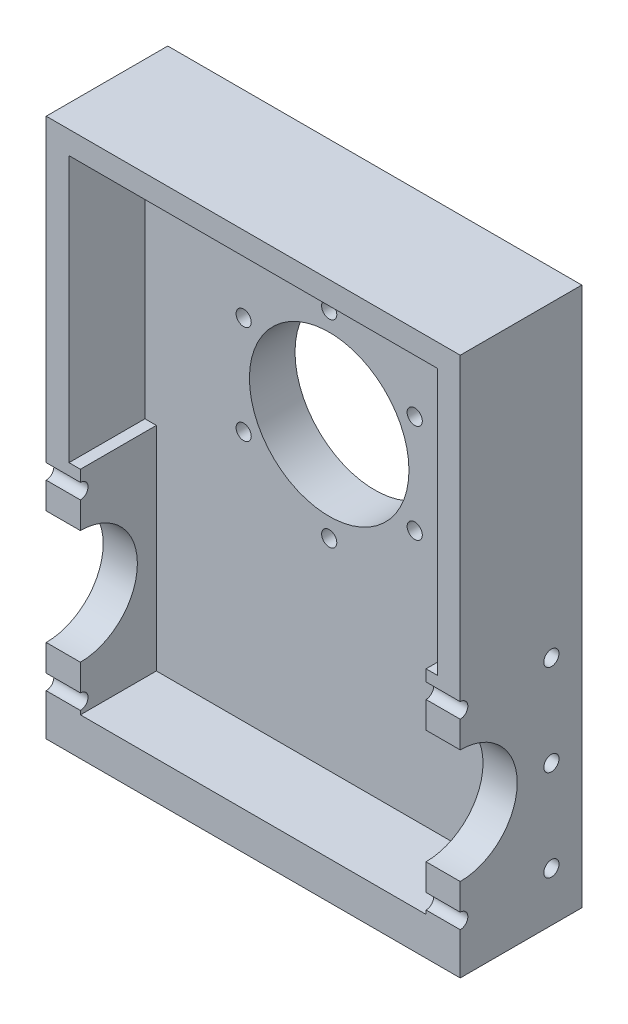
SolidWorks part; units mm, degrees
ref_plane "Front Plane" through (0, 0, 0) normal (0, 0, 1) x (1, 0, 0)
ref_plane "Top Plane" through (0, 0, 0) normal (0, 1, 0) x (1, 0, 0)
ref_plane "Right Plane" through (0, 0, 0) normal (1, 0, 0) x (0, 0, -1)
sketch "Sketch1" plane through (0, 0, 0) normal (0, 0, 1) x (1, 0, 0)
  line L0 (0, 0) -> (0, -52) construction
  line L2 (-48.5, -65) -> (48.5, -65)
  line L3 (-48.5, -65) -> (-48.5, 65)
  line L4 (-48.5, 65) -> (48.5, 65)
  line L5 (48.5, -65) -> (48.5, 65)
  line L6 (-48.5, -65) -> (48.5, 65) construction
  line L7 (-48.5, 65) -> (48.5, -65) construction
  dimension "D1" = 52
  dimension "D2" = 130
  dimension "D3" = 97
extrude "Boss-Extrude1" add sketch "Sketch1" along normal blind 12
sketch "Sketch8" plane through (0, 0, 12) normal (0, 0, 1) x (1, 0, 0)
  line L0 (0, 65) -> (0, 18) construction
  line L1 (48.5, 65) -> (-48.5, 65) construction
  circle A0 centre (0, 18) radius 43.5
  dimension "D2" = 87
  dimension "D1" = 47
sketch "Sketch9" plane through (0, 0, 12) normal (0, 0, 1) x (1, 0, 0)
  line L0 (0, 65) -> (0, 18) construction
  circle A0 centre (0, 18) radius 21
  circle A1 centre (0, 44) radius 2
  circle A7 centre (22.5167, 31) radius 2
  circle A8 centre (22.5167, 5) radius 2
  circle A9 centre (0, -8) radius 2
  circle A10 centre (-22.5167, 5) radius 2
  circle A11 centre (-22.5167, 31) radius 2
  point P19 (8.6603, 13)
  point P21 (0, 18)
  dimension "D1" = 42
  dimension "D2" = 4
  dimension "D3" = 26
  dimension "D4" = 6
extrude "Cut-Extrude2" cut sketch "Sketch9" against normal blind 12
sketch "Sketch11" plane through (0, 0, 0) normal (0, 0, 1) x (1, 0, 0)
  line L0 (-54.5, 71) -> (54.5, 71)
  line L1 (-48.5, -65) -> (48.5, -65)
  line L2 (-48.5, -65) -> (-48.5, 65)
  line L3 (-48.5, 65) -> (48.5, 65)
  line L4 (48.5, -65) -> (48.5, 65)
  line L5 (-48.5, -65) -> (48.5, 65) construction
  line L6 (-48.5, 65) -> (48.5, -65) construction
  line L7 (54.5, -71) -> (54.5, 71)
  line L8 (-54.5, -71) -> (54.5, -71)
  line L9 (-54.5, -71) -> (-54.5, 71)
  point P0 (0, 0)
  dimension "D1" = 6
extrude "Boss-Extrude4" add sketch "Sketch11" along normal blind 32
sketch "Sketch14" plane through (-54.5, 0, 0) normal (-1, 0, 0) x (0, 0, 1)
  line L0 (32, 71) -> (32, -71) construction
  line L1 (32, -71) -> (0, -71) construction
  circle A0 centre (32, -34) radius 15
  point P20 (32, -34)
  point P21 (34.6699, -46.5)
  point P22 (35.5, -27.9378)
  dimension "D1" = 30
  dimension "D2" = 37
sketch "Sketch18" plane through (-48.5, 0, 0) normal (1, 0, 0) x (0, 0, -1)
  line L0 (-12, 65) -> (-12, -65) construction
  line L1 (-32, -65) -> (-12, -65)
  line L2 (-32, -65) -> (-32, -5)
  line L3 (-32, -5) -> (-12, -5)
  line L4 (-12, -65) -> (-12, -5)
  dimension "D1" = 60
extrude "Boss-Extrude5" add sketch "Sketch18" along normal blind 3
mirror "Mirror1" about plane through (0, 0, 0) normal (1, 0, 0) of "Boss-Extrude5"
extrude "Cut-Extrude5" cut sketch "Sketch14" against normal through all
sketch "Sketch20" plane through (0, -65, 0) normal (0, 1, 0) x (1, 0, 0)
  line L1 (-45.5, -12) -> (45.5, -12)
  line L2 (-45.5, -12) -> (-45.5, -32)
  line L3 (-45.5, -32) -> (45.5, -32)
  line L4 (45.5, -12) -> (45.5, -32)
extrude "Boss-Extrude6" add sketch "Sketch20" along normal blind 4
sketch "Sketch21" plane through (-54.5, 0, 0) normal (-1, 0, 0) x (0, 0, 1)
  line L0 (32, -34) -> (32, -10) construction
  line L1 (32, 71) -> (32, -19) construction
  line L2 (0, -34) -> (64.9981, -34) construction
  line L3 (0, 71) -> (0, -71) construction
  circle A0 centre (32, -10) radius 2
  circle A1 centre (8, -10) radius 2
  circle A2 centre (56, -10) radius 2
  circle A3 centre (56, -58) radius 2
  circle A4 centre (32, -58) radius 2
  circle A5 centre (8, -58) radius 2
  circle A6 centre (8, -34) radius 2
  dimension "D2" = 4
  dimension "D3" = 4
  dimension "D4" = 24
  dimension "D5" = 4
  dimension "D6" = 24
  dimension "D7" = 4
  dimension "D1" = 24
extrude "Cut-Extrude6" cut sketch "Sketch21" against normal blind 9
mirror "Mirror2" about plane through (0, 0, 0) normal (1, 0, 0) of "Cut-Extrude6"
